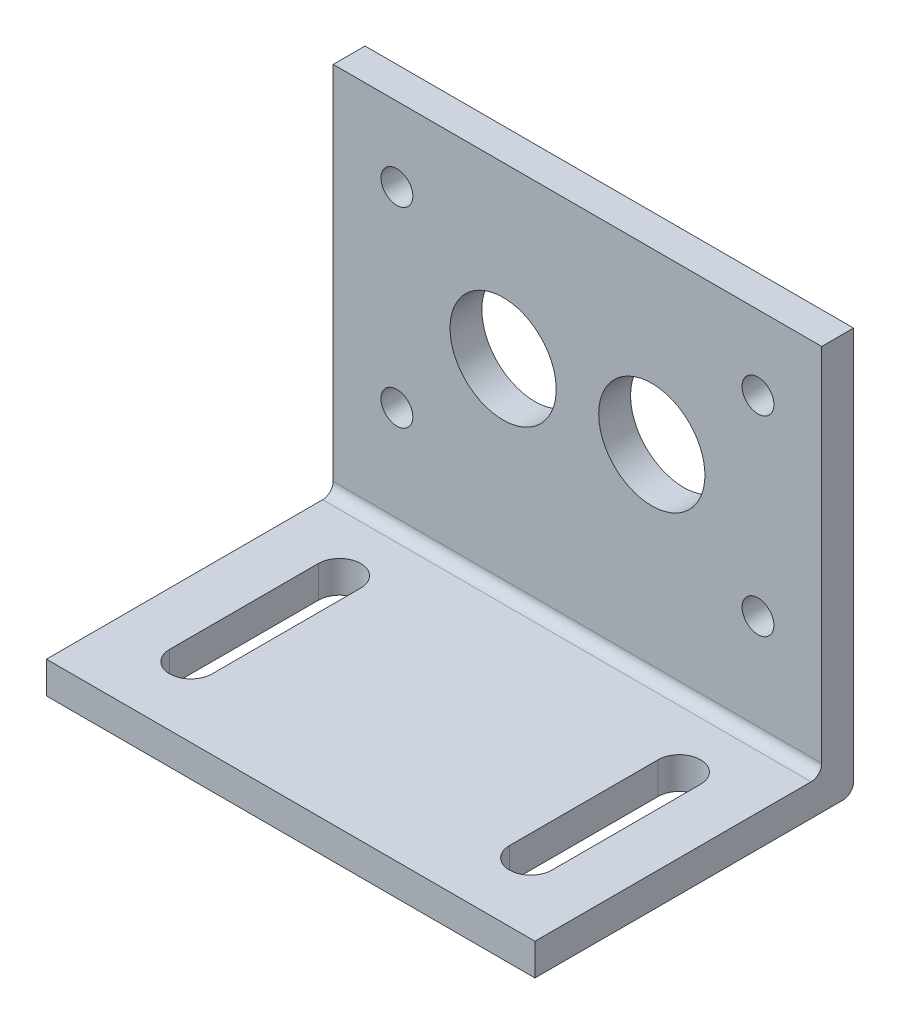
SolidWorks part; units mm, degrees
ref_plane "前视基准面" through (0, 0, 0) normal (0, 0, 1) x (1, 0, 0)
ref_plane "上视基准面" through (0, 0, 0) normal (0, 1, 0) x (1, 0, 0)
ref_plane "右视基准面" through (0, 0, 0) normal (1, 0, 0) x (0, 0, -1)
other "Configuration Table"
sketch "草图1" plane through (0, 0, 0) normal (0, 1, 0) x (1, 0, 0)
  line L1 (-23, -15) -> (23, -15)
  line L2 (-23, -15) -> (-23, 15)
  line L3 (-23, 15) -> (23, 15)
  line L4 (23, -15) -> (23, 15)
  line L5 (-23, -15) -> (23, 15) construction
  line L6 (-23, 15) -> (23, -15) construction
  point P0 (0, 0)
  dimension "D1" = 30
  dimension "D2" = 46
extrude "凸台-拉伸1" add sketch "草图1" along normal blind 3
sketch "草图2" plane through (0, 0, -15) normal (0, 0, -1) x (-1, 0, 0)
  line L0 (-23, 0) -> (23, 0) construction
  line L1 (-23, 38) -> (23, 38)
  line L2 (-23, 38) -> (-23, 0)
  line L3 (-23, 0) -> (23, 0)
  line L4 (23, 38) -> (23, 0)
  line L5 (-23, 38) -> (23, 0) construction
  line L6 (-23, 0) -> (23, 38) construction
  line L7 (23, 3) -> (23, 0) construction
  line L8 (-23, 3) -> (-23, 0) construction
  point P0 (0, 19)
  point P9 (-23, 0)
  dimension "D1" = 38
extrude "凸台-拉伸2" add sketch "草图2" against normal blind 3
fillet "圆角1" radius 1 2 edges at (0, 0, -15) (0, 3, -12)
sketch "草图3" plane through (0, 0, -15) normal (0, 0, -1) x (-1, 0, 0)
  line L0 (23, 38) -> (-23, 38) construction
  line L1 (-17, 13) -> (17, 13) construction
  line L2 (-17, 13) -> (-17, 31) construction
  line L3 (-17, 31) -> (17, 31) construction
  line L4 (17, 13) -> (17, 31) construction
  line L5 (-17, 13) -> (17, 31) construction
  line L6 (-17, 31) -> (17, 13) construction
  line L7 (-7, 22) -> (7, 22) construction
  circle A0 centre (17, 13) radius 1.5
  circle A1 centre (17, 31) radius 1.5
  circle A2 centre (-17, 31) radius 1.5
  circle A3 centre (-17, 13) radius 1.5
  circle A4 centre (7, 22) radius 5
  circle A5 centre (-7, 22) radius 5
  point P0 (0, 22)
  point P15 (0, 22)
  dimension "D4" = 3
  dimension "D6" = 10
  dimension "D1" = 16
  dimension "D2" = 18
  dimension "D3" = 34
  dimension "D5" = 14
extrude "切除-拉伸1" cut sketch "草图3" against normal blind 3
sketch "草图4" plane through (0, 3, 0) normal (0, 1, 0) x (1, 0, 0)
  line L0 (-16, -8.4) -> (-16, 5.6) construction
  line L1 (-18, -8.4) -> (-18, 5.6)
  line L2 (-14, -8.4) -> (-14, 5.6)
  line L3 (-23, -15) -> (23, -15) construction
  line L4 (-23, 11) -> (-23, -15) construction
  line L5 (0, 0) -> (0, 50000) construction
  line L6 (16, -8.4) -> (16, 5.6) construction
  line L7 (18, -8.4) -> (18, 5.6)
  line L8 (14, -8.4) -> (14, 5.6)
  arc A0 (-18, -8.4) -> (-14, -8.4) centre (-16, -8.4) ccw
  arc A1 (-14, 5.6) -> (-18, 5.6) centre (-16, 5.6) ccw
  arc A2 (18, -8.4) -> (14, -8.4) centre (16, -8.4) cw
  arc A3 (14, 5.6) -> (18, 5.6) centre (16, 5.6) cw
  point P2 (-16, -1.4)
  point P16 (16, -1.4)
  dimension "D1" = 2
  dimension "D2" = 6.6
  dimension "D3" = 14
  dimension "D4" = 5
extrude "切除-拉伸2" cut sketch "草图4" against normal blind 3
